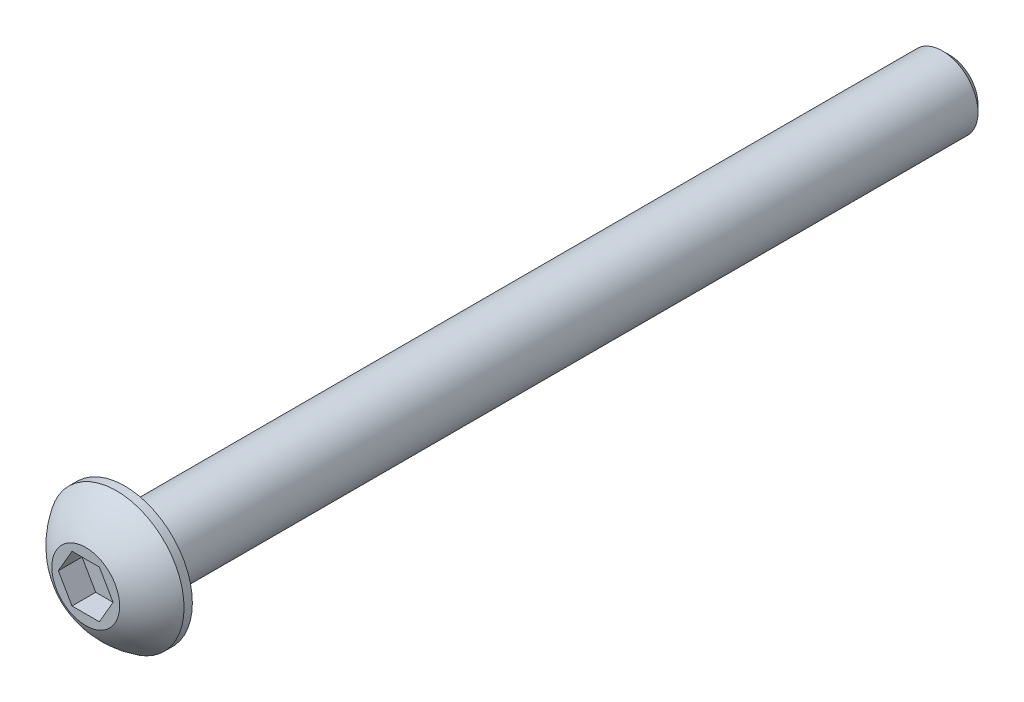
SolidWorks part; units mm, degrees
ref_plane "前视基准面" through (0, 0, 0) normal (0, 0, 1) x (1, 0, 0)
ref_plane "上视基准面" through (0, 0, 0) normal (0, 1, 0) x (1, 0, 0)
ref_plane "右视基准面" through (0, 0, 0) normal (1, 0, 0) x (0, 0, -1)
sketch "草图1" plane through (0, 0, 0) normal (1, 0, 0) x (0, 0, -1)
  line L0 (0, 1.5) -> (0, 2.85)
  line L1 (0, 2.85) -> (-0.35, 2.85)
  line L2 (0, 0) -> (-1.65, 0)
  line L3 (-1.65, 0) -> (-1.65, 1.43)
  line L4 (0, 0) -> (34.8, 0)
  line L5 (34.8, 0) -> (34.8, 1.5)
  line L6 (34.8, 1.5) -> (0, 1.5)
  arc A0 (-1.65, 1.43) -> (-0.35, 2.85) centre (1.5203, -0.1673) cw
  dimension "D4" = 3.55
  dimension "D1" = 2.85
  dimension "D2" = 0.35
  dimension "D3" = 1.43
  dimension "D5" = 1.65
  dimension "D6" = 34.8
  dimension "D7" = 1.5
revolve "旋转1" add sketch "草图1" angle 360 about L4
cosmetic thread "装饰螺纹线2" parameters "D1"=3.5, "D2"=2.439
sketch "草图2" plane through (0, 0, 1.65) normal (0, 0, 1) x (1, 0, 0)
  line L1 (-0.5774, 1) -> (-1.1547, 0)
  line L2 (-1.1547, 0) -> (-0.5774, -1)
  line L3 (-0.5774, -1) -> (0.5774, -1)
  line L4 (0.5774, -1) -> (1.1547, 0)
  line L5 (1.1547, 0) -> (0.5774, 1)
  line L6 (0.5774, 1) -> (-0.5774, 1)
  circle A0 centre (0, 0) radius 1 construction
  dimension "D1" = 1
extrude "切除-拉伸1" cut sketch "草图2" against normal blind 1
chamfer "倒角2" distance 0.3 angle 45 1 edges at (1.5, 0, -34.8)
